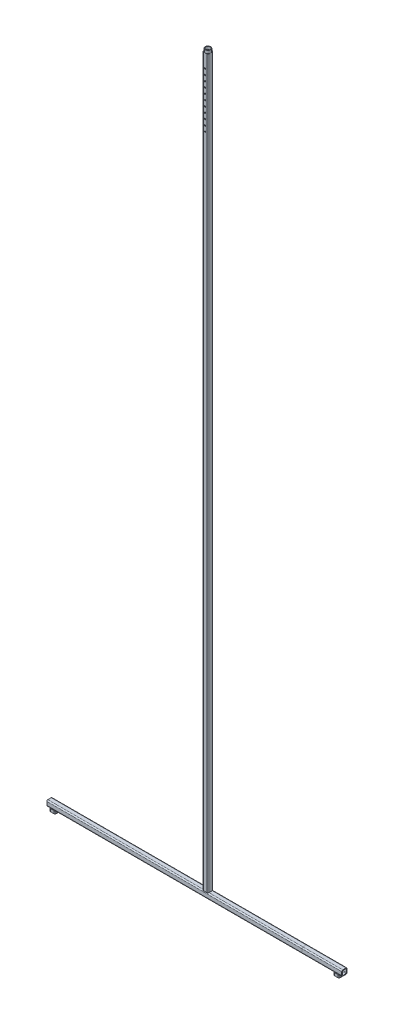
SolidWorks part; units mm, degrees
material "ASTM A36 Steel"
ref_plane "Front Plane" through (0, 0, 0) normal (0, 0, 1) x (1, 0, 0)
ref_plane "Top Plane" through (0, 0, 0) normal (0, 1, 0) x (1, 0, 0)
ref_plane "Right Plane" through (0, 0, 0) normal (1, 0, 0) x (0, 0, -1)
sketch "Sketch2" plane through (0, 0, 0) normal (0, 0, 1) x (1, 0, 0)
  line L0 (385.4461, 689.476) -> (385.4461, -1970.524)
  line L2 (-174.5539, -1990.524) -> (-174.5539, -2000.524)
  line L3 (865.4461, -1990.524) -> (865.4461, -2000.524)
  line L4 (739.4461, -1980.524) -> (-194.5539, -1980.524)
  line L5 (739.4461, -1980.524) -> (885.4461, -1980.524)
  dimension "D1" = 2660
  dimension "D4" = 20
  dimension "D5" = 20
  dimension "D6" = 500
other "Square tube 20 X 20 X 2(1)"
ref_plane "Plane2" through (385.4461, 689.476, 0) normal (0, -1, 0) x (1, 0, 0)
sketch "Sketch1" plane through (385.4461, 689.476, 0) normal (0, -1, 0) x (1, 0, 0)
  line L0 (-6, -8) -> (6, -8)
  line L1 (-8, -6) -> (-8, 6)
  line L2 (6, 8) -> (-6, 8)
  line L3 (8, 6) -> (8, -6)
  line L4 (-6, -10) -> (6, -10)
  line L5 (-10, -6) -> (-10, 6)
  line L6 (6, 10) -> (-6, 10)
  line L7 (10, 6) -> (10, -6)
  arc A0 (10, 6) -> (6, 10) centre (6, 6) ccw
  arc A1 (6, -10) -> (10, -6) centre (6, -6) ccw
  arc A2 (-10, -6) -> (-6, -10) centre (-6, -6) ccw
  arc A3 (-6, 10) -> (-10, 6) centre (-6, 6) ccw
  arc A4 (-6, 8) -> (-8, 6) centre (-6, 6) ccw
  arc A5 (8, 6) -> (6, 8) centre (6, 6) ccw
  arc A6 (6, -8) -> (8, -6) centre (6, -6) ccw
  arc A7 (-8, -6) -> (-6, -8) centre (-6, -6) ccw
  point P0 (-10, 0)
  point P1 (10, 0)
  point P2 (0, 10)
  point P3 (0, -10)
  point P4 (0, 0)
  point P5 (-10, -10)
  point P6 (10, -10)
  point P7 (10, 10)
  point P8 (-10, 10)
  point P33 (0, 0)
  dimension "D1" = 4
  dimension "Thickness" = 2
  dimension "V_leg" = 20
other "Square tube 20 X 20 X 2(2)"
ref_plane "Plane3" through (739.4461, -1980.524, 0) normal (-1, 0, 0) x (0, -1, 0)
sketch "Sketch11" plane through (739.4461, -1980.524, 0) normal (-1, 0, 0) x (0, -1, 0)
  line L0 (-6, -8) -> (6, -8)
  line L1 (-8, -6) -> (-8, 6)
  line L2 (6, 8) -> (-6, 8)
  line L3 (8, 6) -> (8, -6)
  line L4 (-6, -10) -> (6, -10)
  line L5 (-10, -6) -> (-10, 6)
  line L6 (6, 10) -> (-6, 10)
  line L7 (10, 6) -> (10, -6)
  arc A0 (10, 6) -> (6, 10) centre (6, 6) ccw
  arc A1 (6, -10) -> (10, -6) centre (6, -6) ccw
  arc A2 (-10, -6) -> (-6, -10) centre (-6, -6) ccw
  arc A3 (-6, 10) -> (-10, 6) centre (-6, 6) ccw
  arc A4 (-6, 8) -> (-8, 6) centre (-6, 6) ccw
  arc A5 (8, 6) -> (6, 8) centre (6, 6) ccw
  arc A6 (6, -8) -> (8, -6) centre (6, -6) ccw
  arc A7 (-8, -6) -> (-6, -8) centre (-6, -6) ccw
  point P0 (-10, 0)
  point P1 (10, 0)
  point P2 (0, 10)
  point P3 (0, -10)
  point P4 (0, 0)
  point P5 (-10, -10)
  point P6 (10, -10)
  point P7 (10, 10)
  point P8 (-10, 10)
  point P33 (0, 0)
  dimension "D1" = 4
  dimension "Thickness" = 2
  dimension "V_leg" = 20
other "Square tube 20 X 20 X 2(4)"
ref_plane "Plane5" through (-174.5539, -1990.524, 0) normal (0, -1, 0) x (1, 0, 0)
sketch "Sketch13" plane through (-174.5539, -1990.524, 0) normal (0, -1, 0) x (1, 0, 0)
  line L0 (-6, -8) -> (6, -8)
  line L1 (-8, -6) -> (-8, 6)
  line L2 (6, 8) -> (-6, 8)
  line L3 (8, 6) -> (8, -6)
  line L4 (-6, -10) -> (6, -10)
  line L5 (-10, -6) -> (-10, 6)
  line L6 (6, 10) -> (-6, 10)
  line L7 (10, 6) -> (10, -6)
  arc A0 (10, 6) -> (6, 10) centre (6, 6) ccw
  arc A1 (6, -10) -> (10, -6) centre (6, -6) ccw
  arc A2 (-10, -6) -> (-6, -10) centre (-6, -6) ccw
  arc A3 (-6, 10) -> (-10, 6) centre (-6, 6) ccw
  arc A4 (-6, 8) -> (-8, 6) centre (-6, 6) ccw
  arc A5 (8, 6) -> (6, 8) centre (6, 6) ccw
  arc A6 (6, -8) -> (8, -6) centre (6, -6) ccw
  arc A7 (-8, -6) -> (-6, -8) centre (-6, -6) ccw
  point P0 (-10, 0)
  point P1 (10, 0)
  point P2 (0, 10)
  point P3 (0, -10)
  point P4 (0, 0)
  point P5 (-10, -10)
  point P6 (10, -10)
  point P7 (10, 10)
  point P8 (-10, 10)
  point P33 (0, 0)
  dimension "D1" = 4
  dimension "Thickness" = 2
  dimension "V_leg" = 20
sketch "Sketch14" plane through (0, 0, -10) normal (0, 0, -1) x (-1, 0, 0)
  line L0 (-379.4461, 689.476) -> (-391.4461, 689.476) construction
  circle A0 centre (-384.8471, 639.476) radius 2.5
  dimension "D1" = 50
extrude "Cut-Extrude1" cut sketch "Sketch14" against normal through all both and the other way through all
pattern_linear "LPattern1" count 11 spacing 20 along (0, -1, 0) of "Cut-Extrude1"
sketch "Sketch16" plane through (0, 689.476, 0) normal (0, 1, 0) x (1, 0, 0)
  circle A0 centre (385.4461, 0) radius 10
  circle A1 centre (385.4461, 0) radius 8
extrude "Boss-Extrude1" add sketch "Sketch16" along normal blind 10 separate body
ref_plane "Plane6" through (0, 0, 0) normal (0, 0, 1) x (1, 0, 0)
sketch "Sketch17" plane through (0, 0, 0) normal (0, 0, 1) x (1, 0, 0)
  line L0 (-174.5539, -1990.524) -> (-174.5539, -2000.524)
  line L1 (-194.5539, -1990.524) -> (739.4461, -1990.524) construction
  line L2 (-194.5539, -1986.524) -> (-194.5539, -1990.524) construction
  dimension "D1" = 10
  dimension "D2" = 20
other "Square tube 20 X 20 X 2(13)"
ref_plane "Plane7" through (-174.5539, -1990.524, 0) normal (0, -1, 0) x (1, 0, 0)
sketch "Sketch19" plane through (-174.5539, -1990.524, 0) normal (0, -1, 0) x (1, 0, 0)
  line L0 (-6, -8) -> (6, -8)
  line L1 (-8, -6) -> (-8, 6)
  line L2 (6, 8) -> (-6, 8)
  line L3 (8, 6) -> (8, -6)
  line L4 (-6, -10) -> (6, -10)
  line L5 (-10, -6) -> (-10, 6)
  line L6 (6, 10) -> (-6, 10)
  line L7 (10, 6) -> (10, -6)
  arc A0 (10, 6) -> (6, 10) centre (6, 6) ccw
  arc A1 (6, -10) -> (10, -6) centre (6, -6) ccw
  arc A2 (-10, -6) -> (-6, -10) centre (-6, -6) ccw
  arc A3 (-6, 10) -> (-10, 6) centre (-6, 6) ccw
  arc A4 (-6, 8) -> (-8, 6) centre (-6, 6) ccw
  arc A5 (8, 6) -> (6, 8) centre (6, 6) ccw
  arc A6 (6, -8) -> (8, -6) centre (6, -6) ccw
  arc A7 (-8, -6) -> (-6, -8) centre (-6, -6) ccw
  point P0 (-10, 0)
  point P1 (10, 0)
  point P2 (0, 10)
  point P3 (0, -10)
  point P4 (0, 0)
  point P5 (-10, -10)
  point P6 (10, -10)
  point P7 (10, 10)
  point P8 (-10, 10)
  point P33 (0, 0)
  dimension "D1" = 4
  dimension "Thickness" = 2
  dimension "V_leg" = 20
sketch "Sketch20" plane through (0, 0, 0) normal (0, 0, 1) x (1, 0, 0)
  line L0 (865.4461, -1990.524) -> (865.4461, -2000.524)
  line L1 (739.4461, -1990.524) -> (885.4461, -1990.524) construction
  line L2 (885.4461, -1990.524) -> (885.4461, -1986.524) construction
  dimension "D1" = 10
  dimension "D2" = 20
other "Square tube 20 X 20 X 2(14)"
ref_plane "Plane8" through (865.4461, -1990.524, 0) normal (0, -1, 0) x (1, 0, 0)
sketch "Sketch110" plane through (865.4461, -1990.524, 0) normal (0, -1, 0) x (1, 0, 0)
  line L0 (-6, -8) -> (6, -8)
  line L1 (-8, -6) -> (-8, 6)
  line L2 (6, 8) -> (-6, 8)
  line L3 (8, 6) -> (8, -6)
  line L4 (-6, -10) -> (6, -10)
  line L5 (-10, -6) -> (-10, 6)
  line L6 (6, 10) -> (-6, 10)
  line L7 (10, 6) -> (10, -6)
  arc A0 (10, 6) -> (6, 10) centre (6, 6) ccw
  arc A1 (6, -10) -> (10, -6) centre (6, -6) ccw
  arc A2 (-10, -6) -> (-6, -10) centre (-6, -6) ccw
  arc A3 (-6, 10) -> (-10, 6) centre (-6, 6) ccw
  arc A4 (-6, 8) -> (-8, 6) centre (-6, 6) ccw
  arc A5 (8, 6) -> (6, 8) centre (6, 6) ccw
  arc A6 (6, -8) -> (8, -6) centre (6, -6) ccw
  arc A7 (-8, -6) -> (-6, -8) centre (-6, -6) ccw
  point P0 (-10, 0)
  point P1 (10, 0)
  point P2 (0, 10)
  point P3 (0, -10)
  point P4 (0, 0)
  point P5 (-10, -10)
  point P6 (10, -10)
  point P7 (10, 10)
  point P8 (-10, 10)
  point P33 (0, 0)
  dimension "D1" = 4
  dimension "Thickness" = 2
  dimension "V_leg" = 20
